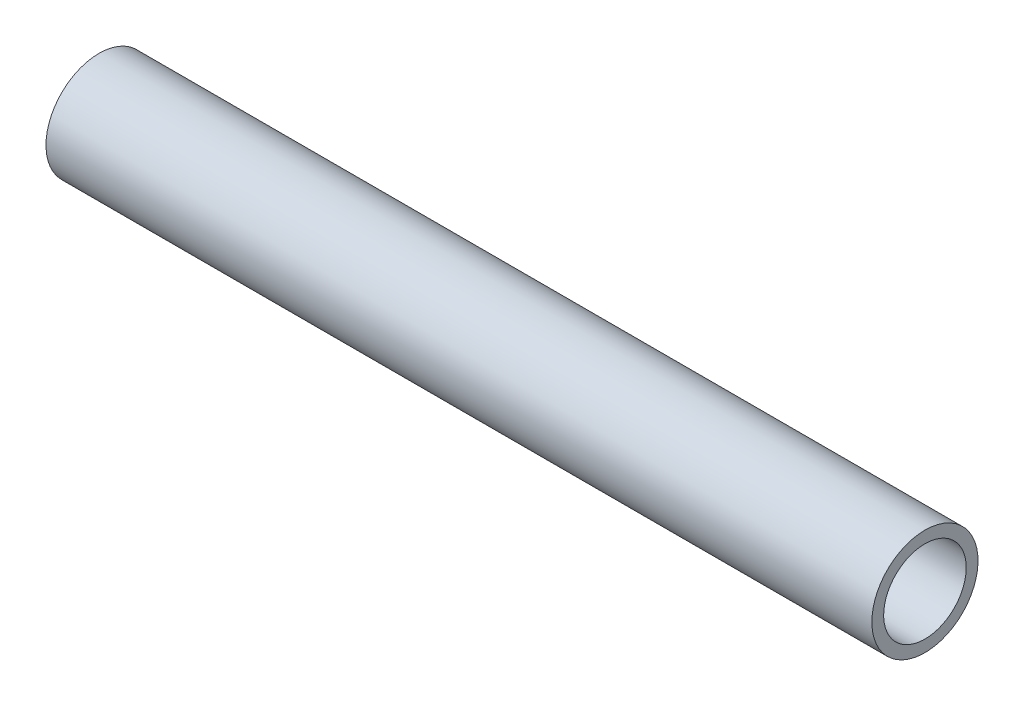
SolidWorks part; units mm, degrees
ref_plane "Front Plane" through (0, 0, 0) normal (0, 0, 1) x (1, 0, 0)
ref_plane "Top Plane" through (0, 0, 0) normal (0, 1, 0) x (1, 0, 0)
ref_plane "Right Plane" through (0, 0, 0) normal (1, 0, 0) x (0, 0, -1)
sketch "Sketch1" plane through (0, 0, 0) normal (0, 0, 1) x (1, 0, 0)
  line L0 (0, 0) -> (6000, 0) construction
  line L1 (1900, 140) -> (1900, 180)
  line L2 (1900, 180) -> (4700, 180)
  line L3 (4700, 180) -> (4700, 140)
  line L4 (4700, 140) -> (1900, 140)
revolve "Revolve1" add sketch "Sketch1" angle 360 about L0
